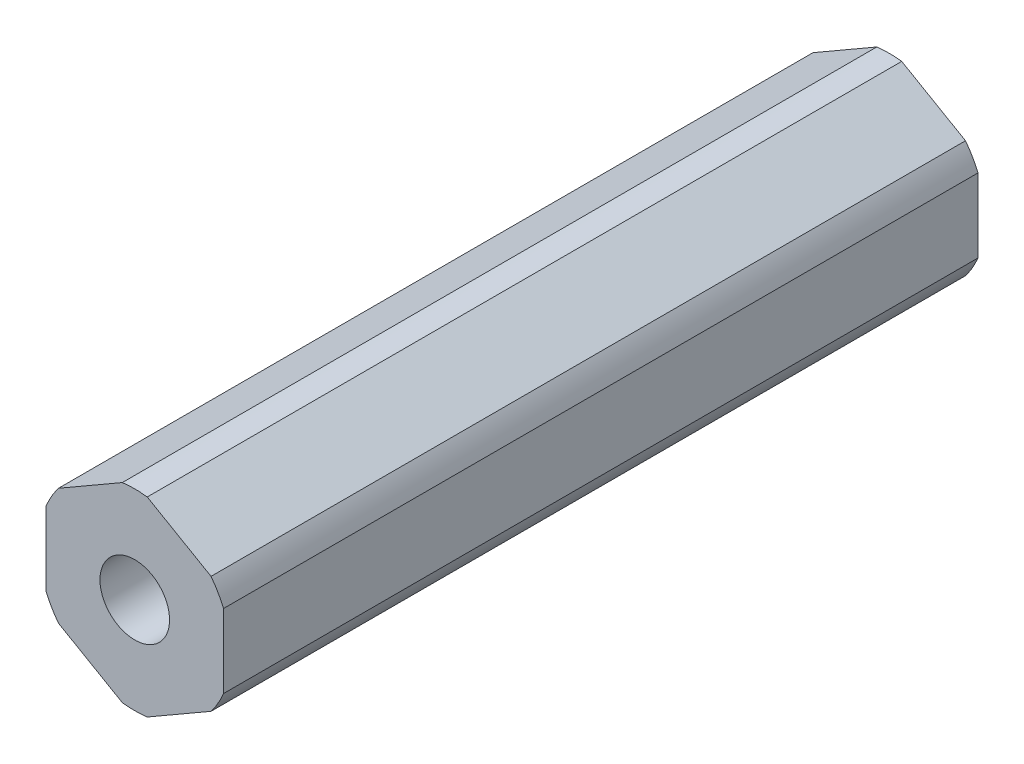
SolidWorks part; units mm, degrees
material "6061-T6 (SS)"
ref_plane "Front Plane" through (0, 0, 0) normal (0, 0, 1) x (1, 0, 0)
ref_plane "Top Plane" through (0, 0, 0) normal (0, 1, 0) x (1, 0, 0)
ref_plane "Right Plane" through (0, 0, 0) normal (1, 0, 0) x (0, 0, -1)
sketch "Sketch1" plane through (0, 0, 0) normal (0, 0, 1) x (1, 0, 0)
  line L1 (6.35, 3.6662) -> (0, 7.3323)
  line L2 (0, 7.3323) -> (-6.35, 3.6662)
  line L3 (-6.35, 3.6662) -> (-6.35, -3.6662)
  line L4 (-6.35, -3.6662) -> (0, -7.3323)
  line L5 (0, -7.3323) -> (6.35, -3.6662)
  line L6 (6.35, -3.6662) -> (6.35, 3.6662)
  circle A0 centre (0, 0) radius 6.35 construction
  circle A1 centre (0, 0) radius 6.875
  dimension "D1" = 13.75
  dimension "D2" = 12.7
extrude "Boss-Extrude1" add sketch "Sketch1" along normal blind 53.975 contours L6 A1 L1 L2 L3 L4 L5
sketch "Sketch2" plane through (0, 0, 0) normal (0, 0, -1) x (-1, 0, 0)
  circle A0 centre (0, 0) radius 2.4892
  dimension "D1" = 4.9784
extrude "Cut-Extrude1" cut sketch "Sketch2" against normal through all and the other way through all
equation "\"D1@Sketch1\"=13.75mm"
